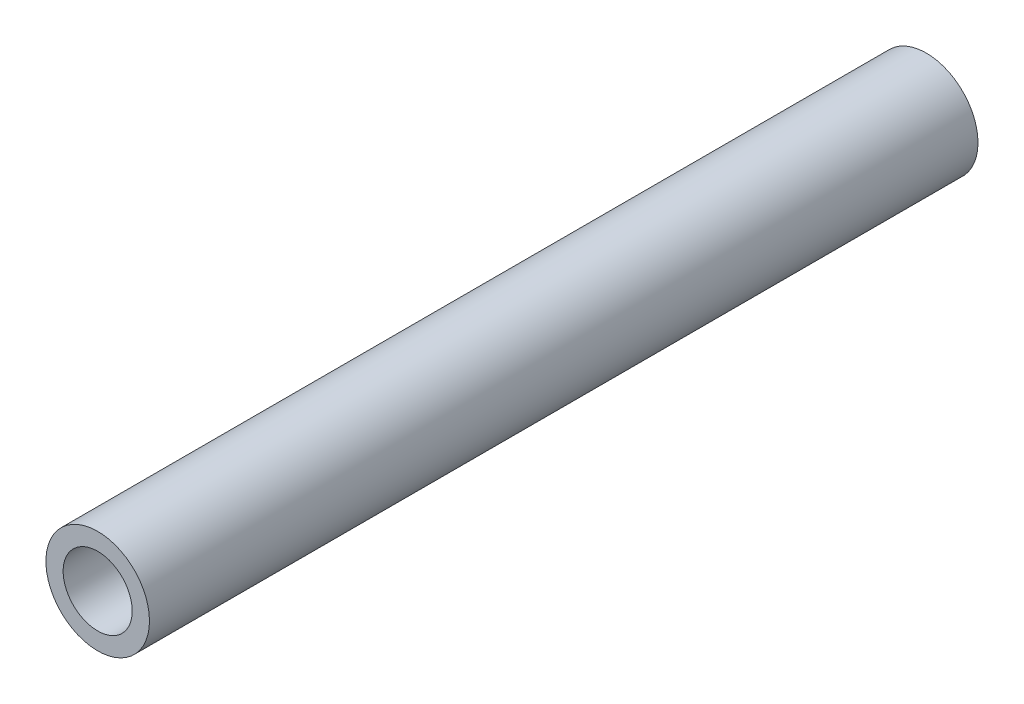
SolidWorks part; units mm, degrees
material "BUTYL"
ref_plane "Front" through (0, 0, 0) normal (0, 0, 1) x (1, 0, 0)
ref_plane "Top" through (0, 0, 0) normal (0, 1, 0) x (1, 0, 0)
ref_plane "Right" through (0, 0, 0) normal (1, 0, 0) x (0, 0, -1)
sketch "Sketch1" plane through (0, 0, 0) normal (0, 0, 1) x (1, 0, 0)
  circle A0 centre (0, 0) radius 6
extrude "Boss-Extrude1" add sketch "Sketch1" along normal blind 96 contours A0
sketch "Sketch2" plane through (0, 0, 96) normal (0, 0, 1) x (1, 0, 0)
  circle A0 centre (0, 0) radius 4
extrude "Cut-Extrude1" cut sketch "Sketch2" against normal blind 190
